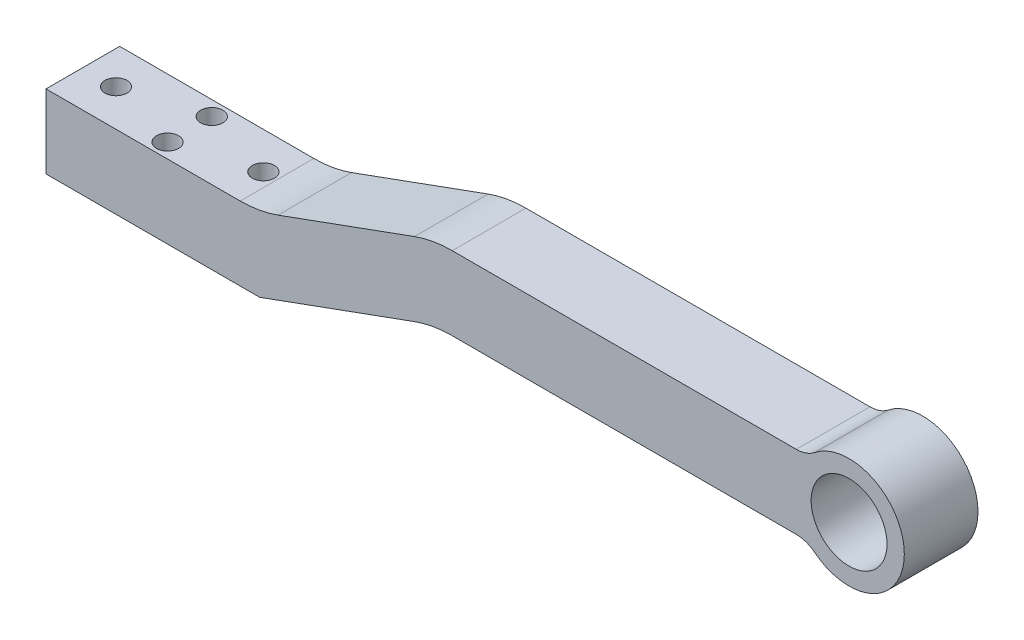
SolidWorks part; units mm, degrees
ref_plane "前视基准面" through (0, 0, 0) normal (0, 0, 1) x (1, 0, 0)
ref_plane "上视基准面" through (0, 0, 0) normal (0, 1, 0) x (1, 0, 0)
ref_plane "右视基准面" through (0, 0, 0) normal (1, 0, 0) x (0, 0, -1)
sketch "Model" plane through (0, 0, 0) normal (0, 0, 1) x (1, 0, 0)
  line L0 (125.2289, 213.5101) -> (183.2289, 213.5101)
  line L1 (183.2289, 213.5101) -> (225.2427, 228.8019)
  line L2 (235.5033, 230.6111) -> (328.9098, 230.6111)
  line L3 (235.5035, 250.611) -> (328.9112, 250.6102)
  line L4 (188.1997, 235.3193) -> (225.2426, 248.8018)
  line L5 (125.2289, 233.5101) -> (177.9391, 233.5101)
  line L6 (125.2289, 233.5101) -> (125.2289, 213.5101)
  arc A0 (333.8904, 228.8716) -> (333.8913, 252.3493) centre (343.2289, 240.6101) ccw
  arc A1 (333.8904, 228.8716) -> (328.9098, 230.6111) centre (328.9098, 222.6111) ccw
  arc A2 (328.9112, 250.6102) -> (333.8913, 252.3493) centre (328.9112, 258.6102) ccw
  circle A3 centre (343.2289, 240.6101) radius 10.3
  arc A4 (177.9391, 233.5101) -> (188.1997, 235.3193) centre (177.9391, 263.5101) ccw
  arc A5 (235.5035, 250.611) -> (225.2426, 248.8018) centre (235.5032, 220.611) ccw
  arc A6 (235.5033, 230.6111) -> (225.2427, 228.8019) centre (235.5033, 200.6111) ccw
extrude "凸台-拉伸1" add sketch "Model" along normal blind 20
sketch "草图2" plane through (0, 213.5101, 0) normal (0, -1, 0) x (1, 0, 0)
  line L0 (125.2289, 10) -> (183.2289, 10) construction
  line L1 (125.2289, 20) -> (125.2289, 0) construction
  line L2 (183.2289, 20) -> (183.2289, 0) construction
  circle A0 centre (134.2289, 10) radius 1.6
  circle A1 centre (174.2289, 10) radius 1.6
  circle A2 centre (154.2289, 16) radius 1.6
  circle A3 centre (154.2289, 4) radius 1.6
  point P16 (125.2289, 4.2072)
  dimension "D1" = 3.2
  dimension "D2" = 3.2
  dimension "D3" = 3.2
  dimension "D4" = 3.2
  dimension "D5" = 40
  dimension "D6" = 9
  dimension "D7" = 6
  dimension "D8" = 6
  dimension "D9" = 12
extrude "切除-拉伸1" cut sketch "草图2" against normal blind 20
sketch "草图3" plane through (0, 233.5101, 0) normal (0, 1, 0) x (1, 0, 0)
  circle A0 centre (134.2289, -10) radius 3
  circle A1 centre (154.2289, -4) radius 3
  circle A2 centre (154.2289, -16) radius 3
  circle A3 centre (174.2289, -10) radius 3
  dimension "D1" = 6
  dimension "D2" = 6
  dimension "D3" = 6
  dimension "D4" = 6
extrude "切除-拉伸2" cut sketch "草图3" against normal blind 8.5
